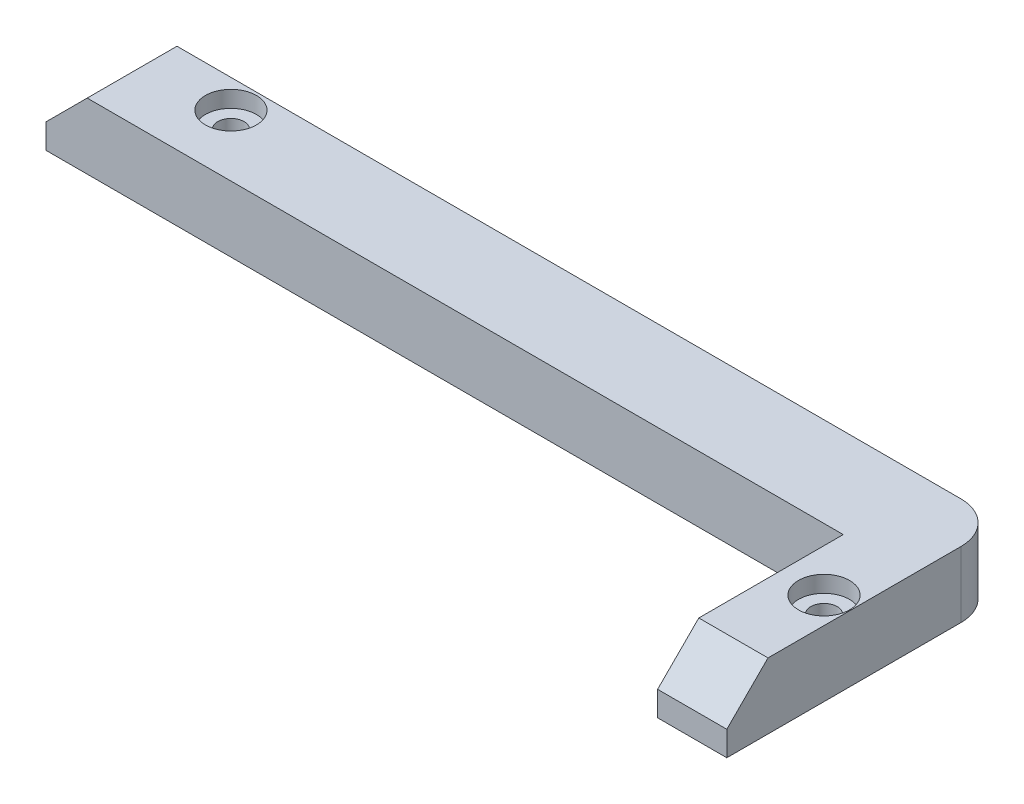
SolidWorks part; units mm, degrees
ref_plane "前视基准面" through (0, 0, 0) normal (0, 0, 1) x (1, 0, 0)
ref_plane "上视基准面" through (0, 0, 0) normal (0, 1, 0) x (1, 0, 0)
ref_plane "右视基准面" through (0, 0, 0) normal (1, 0, 0) x (0, 0, -1)
other "Configuration Table"
sketch "草图1" plane through (0, 0, 0) normal (0, 1, 0) x (1, 0, 0)
  line L1 (0, 0) -> (337.35, 0)
  line L2 (0, 0) -> (0, 116.87)
  line L3 (0, 116.87) -> (337.35, 116.87)
  line L4 (337.35, 0) -> (337.35, 116.87)
  line L5 (6.9, 109.97) -> (330.95, 109.97)
  line L6 (6.9, 109.97) -> (6.9, 6.9)
  line L7 (6.9, 6.9) -> (330.95, 6.9)
  line L8 (330.95, 109.97) -> (330.95, 6.9)
  dimension "D1" = 116.87
  dimension "D2" = 337.35
  dimension "D3" = 6.9
  dimension "D4" = 6.4
  dimension "D5" = 6.9
  dimension "D6" = 6.9
extrude "凸台-拉伸1" add sketch "草图1" along normal blind 8
fillet "圆角1" radius 5 4 edges at (0, 4, 0) (0, 4, -116.87) (337.35, 4, -116.87) (337.35, 4, 0)
sketch "草图2" plane through (0, 8, 0) normal (0, 1, 0) x (1, 0, 0)
  line L0 (167.17, 132.4281) -> (167.17, -13.3473) construction
  line L1 (0, 58.435) -> (337.35, 58.435) construction
  line L2 (0, 111.87) -> (0, 5) construction
  line L3 (337.35, 5) -> (337.35, 111.87) construction
  line L4 (23.7897, 113.42) -> (281.2218, 113.42) construction
  line L5 (3.45, 113.0437) -> (3.45, 3.45) construction
  line L6 (3.45, 3.45) -> (334.15, 3.45) construction
  line L7 (334.15, 3.45) -> (334.15, 110.0858) construction
  line L8 (332.35, 116.87) -> (5, 116.87) construction
  line L9 (330.95, 109.97) -> (6.9, 109.97) construction
  line L10 (6.9, 109.97) -> (6.9, 6.9) construction
  line L11 (6.9, 6.9) -> (330.95, 6.9) construction
  line L12 (5, 0) -> (332.35, 0) construction
  line L13 (330.95, 6.9) -> (330.95, 109.97) construction
  point P26 (87.17, 113.42)
  point P27 (247.17, 113.42)
  point P28 (247.17, 3.45)
  point P29 (87.17, 3.45)
  point P30 (3.45, 18.435)
  point P31 (334.15, 98.435)
  point P32 (3.45, 98.435)
  point P33 (334.15, 18.435)
  dimension "D1" = 167.17
  dimension "D2" = 160
  dimension "D3" = 80
hole_wizard "Ø3.2 (3.2) 直径孔1" positions "草图3" profile "草图4" hole size "Ø3.2" standard "ANSI Metric" end condition through all
sketch "草图3" plane through (0, 8, 0) normal (0, 1, 0) x (1, 0, 0)
  point P0 (3.45, 98.435)
  point P3 (87.17, 113.42)
  point P6 (247.17, 113.42)
  point P9 (334.15, 98.435)
  point P12 (334.15, 18.435)
  point P15 (247.17, 3.45)
  point P18 (87.17, 3.45)
  point P21 (3.45, 18.435)
sketch "草图4" plane through (3.45, 8, -98.435) normal (1, 0, 0) x (0, 0, 1)
  line L0 (0, 0) -> (0, 8)
  line L1 (0, 8) -> (1.6, 8)
  line L2 (1.6, 8) -> (1.6, 0)
  line L5 (1.6, 0) -> (0, 0)
  line L11 (0, -6.35) -> (0, 107.95) construction
  dimension "通孔孔直径" = 3.2
  dimension "通孔孔深度" = 8
sketch "草图5" plane through (0, 0, -109.97) normal (0, 0, 1) x (1, 0, 0)
  line L0 (330.95, 0) -> (6.9, 0) construction
  line L1 (41.9, 0) -> (73.9, 0)
  line L2 (41.9, 0) -> (41.9, 1.5)
  line L3 (41.9, 1.5) -> (73.9, 1.5)
  line L4 (73.9, 0) -> (73.9, 1.5)
  line L5 (6.9, 8) -> (6.9, 0) construction
  dimension "D1" = 35
  dimension "D2" = 32
  dimension "D3" = 1.5
extrude "切除-拉伸1" cut sketch "草图5" against normal through all
sketch "草图6" plane through (0, 0, -109.97) normal (0, 0, 1) x (1, 0, 0)
  line L0 (330.95, 8) -> (6.9, 8) construction
  line L1 (41.9, 0) -> (38.9, 0)
  line L2 (41.9, 0) -> (41.9, 8)
  line L3 (41.9, 8) -> (38.9, 8)
  line L4 (38.9, 0) -> (38.9, 8)
  dimension "D1" = 3
extrude "凸台-拉伸2" add sketch "草图6" along normal up to next
sketch "草图7" plane through (0, 0, -109.97) normal (0, 0, 1) x (1, 0, 0)
  line L1 (73.9, 0) -> (330.95, 0)
  line L2 (73.9, 0) -> (73.9, 8)
  line L3 (73.9, 8) -> (330.95, 8)
  line L4 (330.95, 0) -> (330.95, 8)
extrude "凸台-拉伸3" add sketch "草图7" along normal blind 4
sketch "草图8" plane through (0, 0, 0) normal (0, -1, 0) x (1, 0, 0)
  line L1 (330.95, -105.97) -> (73.9, -105.97)
  line L2 (330.95, -105.97) -> (330.95, -109.97)
  line L3 (330.95, -109.97) -> (73.9, -109.97)
  line L4 (73.9, -105.97) -> (73.9, -109.97)
extrude "凸台-拉伸4" add sketch "草图8" along normal blind 3
sketch "草图9" plane through (0, 8, 0) normal (0, 1, 0) x (1, 0, 0)
  circle A0 centre (137.8085, 107.33) radius 3.5
  circle A1 centre (328.3085, 74.31) radius 3.5
  circle A2 centre (328.3085, 13.35) radius 3.5
  circle A3 centre (262.2685, 9.54) radius 3.5
  circle A4 centre (92.0885, 9.54) radius 3.5
  circle A5 centre (22.2385, 9.54) radius 3.5
  circle A6 centre (9.5385, 23.51) radius 3.5
  circle A7 centre (9.5385, 103.52) radius 3.5
  dimension "D1" = 7
sketch "草图11" plane through (330.95, 0, 0) normal (-1, 0, 0) x (0, 0, 1)
  line L1 (-6.9, 8) -> (-105.97, 8)
  line L2 (-6.9, 8) -> (-6.9, -3)
  line L3 (-6.9, -3) -> (-105.97, -3)
  line L4 (-105.97, 8) -> (-105.97, -3)
extrude "凸台-拉伸5" add sketch "草图11" along normal blind 2
sketch "草图13" plane through (0, 0, -105.97) normal (0, 0, 1) x (1, 0, 0)
  line L0 (328.95, 8) -> (73.9, 8) construction
  line L1 (328.95, -3) -> (286.95, -3)
  line L2 (328.95, -3) -> (328.95, 1.5)
  line L3 (328.95, 1.5) -> (286.95, 1.5)
  line L4 (286.95, -3) -> (286.95, 1.5)
  dimension "D1" = 6.5
  dimension "D2" = 42
extrude "切除-拉伸2" cut sketch "草图13" against normal through all
sketch "草图14" plane through (0, 0, -6.9) normal (0, 0, -1) x (-1, 0, 0)
  line L0 (-41.9, 0) -> (-328.95, 0) construction
  line L1 (-233.95, 0) -> (-112.45, 0)
  line L2 (-233.95, 0) -> (-233.95, 1.5)
  line L3 (-233.95, 1.5) -> (-112.45, 1.5)
  line L4 (-112.45, 0) -> (-112.45, 1.5)
  line L6 (-41.9, 8) -> (-328.95, 8) construction
  line L7 (-328.95, 0) -> (-328.95, 8) construction
  dimension "D1" = 6.5
  dimension "D2" = 95
  dimension "D3" = 216.5
extrude "切除-拉伸3" cut sketch "草图14" against normal through all
sketch "草图16" plane through (0, 0, -109.97) normal (0, 0, 1) x (1, 0, 0)
  line L1 (41.9, 8) -> (73.9, 8)
  line L2 (41.9, 8) -> (41.9, 1.5)
  line L3 (41.9, 1.5) -> (73.9, 1.5)
  line L4 (73.9, 8) -> (73.9, 1.5)
extrude "凸台-拉伸7" add sketch "草图16" along normal up to surface (4 mm away)
sketch "草图17" plane through (330.95, 0, 0) normal (1, 0, 0) x (0, 0, -1)
  line L8 (109.97, -3) -> (109.97, 0)
  line L9 (109.97, 0) -> (6.9, 0)
  line L10 (6.9, 0) -> (6.9, -3)
  line L11 (6.9, -3) -> (109.97, -3)
  line L12 (109.97, -3) -> (109.97, 0)
  line L13 (109.97, 0) -> (6.9, 0)
  line L14 (6.9, 0) -> (6.9, -3)
  line L15 (6.9, -3) -> (109.97, -3)
  dimension "D1" = 0
extrude "切除-拉伸4" cut sketch "草图17" against normal blind 0.1
sketch "草图18" plane through (0, 0, -6.9) normal (0, 0, -1) x (-1, 0, 0)
  line L16 (-233.95, 0) -> (-233.95, 1.5)
  line L17 (-233.95, 1.5) -> (-112.45, 1.5)
  line L18 (-112.45, 1.5) -> (-112.45, 0)
  line L19 (-112.45, 0) -> (-41.9, 0)
  line L20 (-41.9, 0) -> (-41.9, 8)
  line L21 (-41.9, 8) -> (-328.95, 8)
  line L22 (-328.95, 8) -> (-328.95, 0)
  line L23 (-328.95, 0) -> (-233.95, 0)
  line L24 (-233.95, 0) -> (-233.95, 1.5)
  line L25 (-233.95, 1.5) -> (-112.45, 1.5)
  line L26 (-112.45, 1.5) -> (-112.45, 0)
  line L27 (-112.45, 0) -> (-41.9, 0)
  line L28 (-41.9, 0) -> (-41.9, 8)
  line L29 (-41.9, 8) -> (-328.95, 8)
  line L30 (-328.95, 8) -> (-328.95, 0)
  line L31 (-328.95, 0) -> (-233.95, 0)
  dimension "D1" = 0
extrude "凸台-拉伸8" add sketch "草图18" along normal blind 2
sketch "草图19" plane through (0, 0, 0) normal (0, -1, 0) x (1, 0, 0)
  line L0 (112.45, 0) -> (112.45, -8.9) construction
  line L1 (41.9, -8.9) -> (112.45, -8.9)
  line L2 (41.9, -8.9) -> (41.9, -6.9)
  line L3 (41.9, -6.9) -> (112.45, -6.9)
  line L4 (112.45, -8.9) -> (112.45, -6.9)
  line L6 (233.95, -8.9) -> (328.95, -8.9)
  line L7 (233.95, -8.9) -> (233.95, -6.9)
  line L8 (233.95, -6.9) -> (328.95, -6.9)
  line L9 (328.95, -8.9) -> (328.95, -6.9)
  dimension "D1" = 2
extrude "凸台-拉伸9" add sketch "草图19" along normal up to surface (3 mm away) up to face at (329.9, -3, -58.435)
sketch "草图10" plane through (0, -3, 0) normal (0, -1, 0) x (1, 0, 0)
  circle A2 centre (137.8085, -107.33) radius 3.5
  circle A3 centre (137.8085, -107.33) radius 3.5
  dimension "D1" = 0
sketch "草图20" plane through (0, -3, 0) normal (0, -1, 0) x (1, 0, 0)
  circle A58 centre (92.0885, -9.54) radius 3.5
  circle A59 centre (92.0885, -9.54) radius 3.5
  circle A120 centre (262.2685, -9.54) radius 3.5
  circle A121 centre (262.2685, -9.54) radius 3.5
  circle A123 centre (328.3085, -13.35) radius 3.5
  circle A124 centre (328.3085, -13.35) radius 3.5
  circle A126 centre (328.3085, -74.31) radius 3.5
  circle A127 centre (328.3085, -74.31) radius 3.5
  circle A129 centre (137.8085, -107.33) radius 3.5
  circle A130 centre (137.8085, -107.33) radius 3.5
  circle A132 centre (22.2385, -9.54) radius 3.5
  circle A133 centre (22.2385, -9.54) radius 3.5
  circle A135 centre (9.5385, -23.51) radius 3.5
  circle A136 centre (9.5385, -23.51) radius 3.5
  circle A138 centre (9.5385, -103.52) radius 3.5
  circle A139 centre (9.5385, -103.52) radius 3.5
  dimension "D1" = 0
  dimension "D2" = 0
  dimension "D3" = 0
  dimension "D4" = 0
  dimension "D5" = 0
  dimension "D6" = 0
  dimension "D7" = 0
  dimension "D8" = 0
extrude "切除-拉伸5" cut sketch "草图20" against normal blind 4
sketch "草图21" plane through (0, 8, 0) normal (0, 1, 0) x (1, 0, 0)
  circle A2 centre (87.17, 113.42) radius 3.1
  circle A3 centre (87.17, 113.42) radius 3.1
  circle A5 centre (247.17, 113.42) radius 3.1
  circle A6 centre (247.17, 113.42) radius 3.1
  circle A8 centre (334.15, 98.435) radius 3.1
  circle A9 centre (334.15, 98.435) radius 3.1
  circle A11 centre (334.15, 18.435) radius 3.1
  circle A12 centre (334.15, 18.435) radius 3.1
  circle A14 centre (247.17, 3.45) radius 3.1
  circle A15 centre (247.17, 3.45) radius 3.1
  circle A17 centre (87.17, 3.45) radius 3.1
  circle A18 centre (87.17, 3.45) radius 3.1
  circle A20 centre (3.45, 18.435) radius 3.1
  circle A21 centre (3.45, 18.435) radius 3.1
  circle A23 centre (3.45, 98.435) radius 3.1
  circle A24 centre (3.45, 98.435) radius 3.1
  dimension "D1" = 1.5
  dimension "D2" = 1.5
  dimension "D3" = 1.5
  dimension "D4" = 1.5
  dimension "D5" = 1.5
  dimension "D6" = 1.5
  dimension "D7" = 1.5
  dimension "D8" = 1.5
extrude "切除-拉伸6" cut sketch "草图21" against normal blind 2
ref_plane "基准面1" through (0, 4, 0) normal (0, 1, 0) x (1, 0, 0)
sketch "草图22" plane through (0, 4, 0) normal (0, 1, 0) x (1, 0, 0)
  line L0 (6.9, 106.97) -> (12.9, 106.97) construction
  line L1 (6.9, 109.97) -> (12.9, 109.97)
  line L2 (6.9, 109.97) -> (6.9, 103.97)
  line L3 (6.9, 103.97) -> (12.9, 103.97)
  line L4 (12.9, 109.97) -> (12.9, 103.97)
  line L5 (38.9, 109.97) -> (32.9, 109.97)
  line L6 (38.9, 109.97) -> (38.9, 103.97)
  line L7 (38.9, 103.97) -> (32.9, 103.97)
  line L8 (32.9, 109.97) -> (32.9, 103.97)
  line L9 (6.9, 6.9) -> (12.9, 6.9)
  line L10 (6.9, 6.9) -> (6.9, 12.9)
  line L11 (6.9, 12.9) -> (12.9, 12.9)
  line L12 (12.9, 6.9) -> (12.9, 12.9)
  line L13 (38.9, 6.9) -> (32.9, 6.9)
  line L14 (38.9, 6.9) -> (38.9, 12.9)
  line L15 (38.9, 12.9) -> (32.9, 12.9)
  line L16 (32.9, 6.9) -> (32.9, 12.9)
  line L17 (32.9, 106.97) -> (38.9, 106.97) construction
  line L18 (6.9, 9.9) -> (12.9, 9.9) construction
  line L19 (32.9, 9.9) -> (38.9, 9.9) construction
  circle A0 centre (9.9, 106.97) radius 1.5
  circle A1 centre (35.9, 106.97) radius 1.5
  circle A2 centre (9.9, 9.9) radius 1.5
  circle A3 centre (35.9, 9.9) radius 1.5
  dimension "D2" = 3
  dimension "D1" = 6
extrude "凸台-拉伸10" add sketch "草图22" along normal offset from surface 2 and the other way offset from surface (3 mm away) 1 up to face at (3.45, 8, -95.335) other way up to face at (16.1954, 0, -50.074)
sketch "草图23" plane through (0, 0, 0) normal (-1, 0, 0) x (0, 0, 1)
  line L0 (-111.87, 0) -> (-5, 0) construction
  line L1 (-58.435, 0) -> (-43.435, 0)
  line L2 (-58.435, 0) -> (-58.435, 1.5)
  line L3 (-58.435, 1.5) -> (-43.435, 1.5)
  line L4 (-43.435, 0) -> (-43.435, 1.5)
  line L6 (-58.435, 0) -> (-68.435, 0)
  line L7 (-58.435, 0) -> (-58.435, 1.5)
  line L8 (-58.435, 1.5) -> (-68.435, 1.5)
  line L9 (-68.435, 0) -> (-68.435, 1.5)
  line M9 (-111.87, 0) -> (-5, 0)
  dimension "D1" = 1.5
  dimension "D2" = 15
  dimension "D3" = 10
extrude "切除-拉伸7" cut sketch "草图23" against normal up to surface (6.9 mm away) contours L9 L2 L8 M9 | L4 L3 L2 M9 up to face at (6.9, 2.875, -48.61)
sketch "草图24" plane through (337.35, 0, 0) normal (1, 0, 0) x (0, 0, -1)
  line L1 (6.9, 0) -> (109.97, 0)
  line L2 (6.9, 0) -> (6.9, -3)
  line L3 (6.9, -3) -> (109.97, -3)
  line L4 (109.97, 0) -> (109.97, -3)
extrude "切除-拉伸8" cut sketch "草图24" against normal through all
sketch "草图25" plane through (0, 8, 0) normal (0, 1, 0) x (1, 0, 0)
  line L1 (232.17, 117.9857) -> (345.6852, 117.9857)
  line L2 (232.17, 117.9857) -> (232.17, 83.435)
  line L3 (232.17, 83.435) -> (345.6852, 83.435)
  line L4 (345.6852, 117.9857) -> (345.6852, 83.435)
  line L5 (-28.704, 160.2755) -> (437.7923, 160.2755)
  line L6 (-28.704, 160.2755) -> (-28.704, -43.3563)
  line L7 (-28.704, -43.3563) -> (437.7923, -43.3563)
  line L8 (437.7923, 160.2755) -> (437.7923, -43.3563)
  dimension "D1" = 15
  dimension "D2" = 15
extrude "切除-拉伸9" cut sketch "草图25" against normal through all
chamfer "倒角1" distance 5 angle 45 2 edges at (333.15, 8, -83.435) (232.17, 8, -111.42)
sketch "草图26" plane through (0, 1.5, 0) normal (0, -1, 0) x (1, 0, 0)
  line L4 (328.95, -105.97) -> (286.95, -105.97)
  line L5 (286.95, -105.97) -> (286.95, -116.87)
  line L6 (286.95, -116.87) -> (328.95, -116.87)
  line L7 (328.95, -116.87) -> (328.95, -105.97)
  line L8 (328.95, -105.97) -> (286.95, -105.97)
  line L9 (286.95, -105.97) -> (286.95, -116.87)
  line L10 (286.95, -116.87) -> (328.95, -116.87)
  line L11 (328.95, -116.87) -> (328.95, -105.97)
  dimension "D1" = 0
extrude "凸台-拉伸11" add sketch "草图26" along normal up to surface (1.5 mm away) up to face at (247.17, 0, -111.82)
